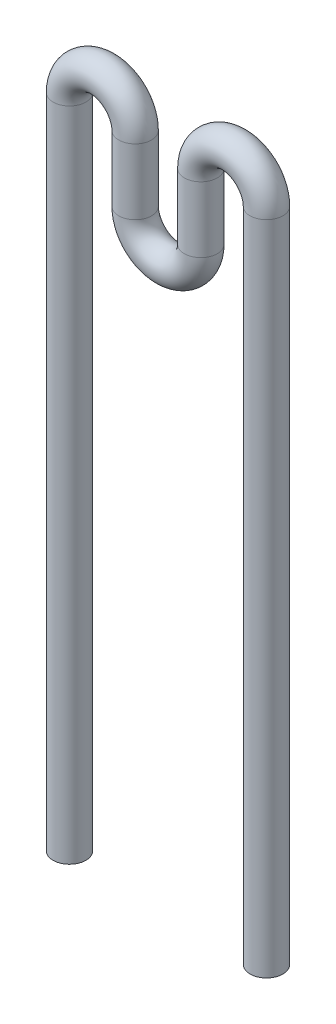
SolidWorks part; units mm, degrees
material "Copper"
ref_plane "Front Plane" through (0, 0, 0) normal (0, 0, 1) x (1, 0, 0)
ref_plane "Top Plane" through (0, 0, 0) normal (0, 1, 0) x (1, 0, 0)
ref_plane "Right Plane" through (0, 0, 0) normal (1, 0, 0) x (0, 0, -1)
sketch "Sketch1" plane through (0, 0, 0) normal (0, 0, 1) x (1, 0, 0)
  line L0 (0, 0) -> (0, 200)
  line L1 (20, 200) -> (20, 180)
  line L2 (40, 180) -> (40, 200)
  line L3 (60, 200) -> (60, 0)
  arc A0 (0, 200) -> (20, 200) centre (10, 200) cw
  arc A1 (20, 180) -> (40, 180) centre (30, 180) ccw
  arc A2 (40, 200) -> (60, 200) centre (50, 200) cw
  point P2 (0, 0)
  point P12 (0, 0)
  dimension "D1" = 200
  dimension "D2" = 20
  dimension "D3" = 20
  dimension "D4" = 20
  dimension "D5" = 20
sketch "Sketch8" plane through (0, 0, 0) normal (0, 1, 0) x (1, 0, 0)
  circle A0 centre (0, 0) radius 5
  dimension "D1" = 10
sweep "Sweep3" add profiles "Sketch8" path "Sketch1"
